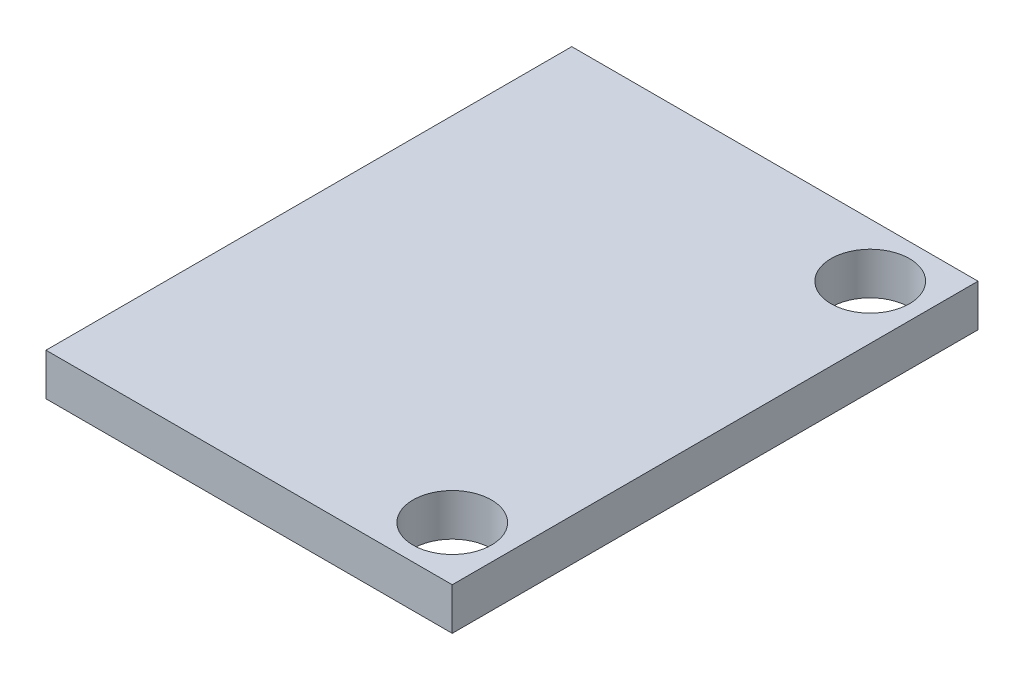
SolidWorks part; units mm, degrees
ref_plane "Front Plane" through (0, 0, 0) normal (0, 0, 1) x (1, 0, 0)
ref_plane "Top Plane" through (0, 0, 0) normal (0, 1, 0) x (1, 0, 0)
ref_plane "Right Plane" through (0, 0, 0) normal (1, 0, 0) x (0, 0, -1)
sketch "Sketch1" plane through (0, 0, 0) normal (0, 1, 0) x (1, 0, 0)
  line L1 (-7.8994, -10.2235) -> (7.8994, -10.2235)
  line L2 (-7.8994, -10.2235) -> (-7.8994, 10.2235)
  line L3 (-7.8994, 10.2235) -> (7.8994, 10.2235)
  line L4 (7.8994, -10.2235) -> (7.8994, 10.2235)
  line L5 (-7.8994, -10.2235) -> (7.8994, 10.2235) construction
  line L6 (-7.8994, 10.2235) -> (7.8994, -10.2235) construction
  point P0 (0, 0)
  dimension "D1" = 20.447
  dimension "D2" = 15.7988
extrude "Boss-Extrude1" add sketch "Sketch1" along normal blind 1.6383
sketch "Sketch2" plane through (0, 1.6383, 0) normal (0, 1, 0) x (1, 0, 0)
  line L0 (0, 0) -> (29.1011, 0) construction
  line L1 (7.8994, -10.2235) -> (7.8994, 10.2235) construction
  line L2 (-7.8994, -10.2235) -> (7.8994, -10.2235) construction
  circle A0 centre (5.8039, -8.128) radius 1.524
  circle A1 centre (5.8039, 8.128) radius 1.524
  dimension "D1" = 3.048
  dimension "D3" = 2.0955
  dimension "D2" = 2.0955
extrude "Cut-Extrude1" cut sketch "Sketch2" against normal blind 1.6383
ref_plane "Plane1" through (0, 0, 0) normal (0, 0, -1) x (-1, 0, 0)
